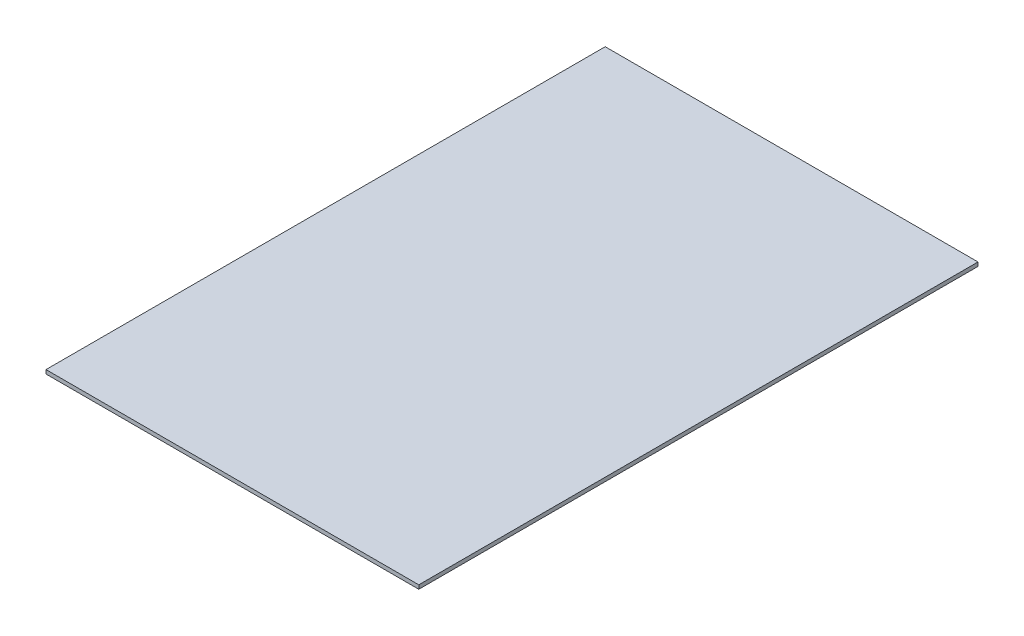
SolidWorks part; units mm, degrees
ref_plane "Front Plane" through (0, 0, 0) normal (0, 0, 1) x (1, 0, 0)
ref_plane "Top Plane" through (0, 0, 0) normal (0, 1, 0) x (1, 0, 0)
ref_plane "Right Plane" through (0, 0, 0) normal (1, 0, 0) x (0, 0, -1)
sketch "Sketch1" plane through (0, 0, 0) normal (0, 1, 0) x (1, 0, 0)
  line L1 (-304.8, -457.2) -> (304.8, -457.2)
  line L2 (-304.8, -457.2) -> (-304.8, 457.2)
  line L3 (-304.8, 457.2) -> (304.8, 457.2)
  line L4 (304.8, -457.2) -> (304.8, 457.2)
  line L5 (-304.8, -457.2) -> (304.8, 457.2) construction
  line L6 (-304.8, 457.2) -> (304.8, -457.2) construction
  point P0 (0, 0)
  dimension "D1" = 609.6
  dimension "D2" = 914.4
extrude "Boss-Extrude1" add sketch "Sketch1" along normal blind 6.35
